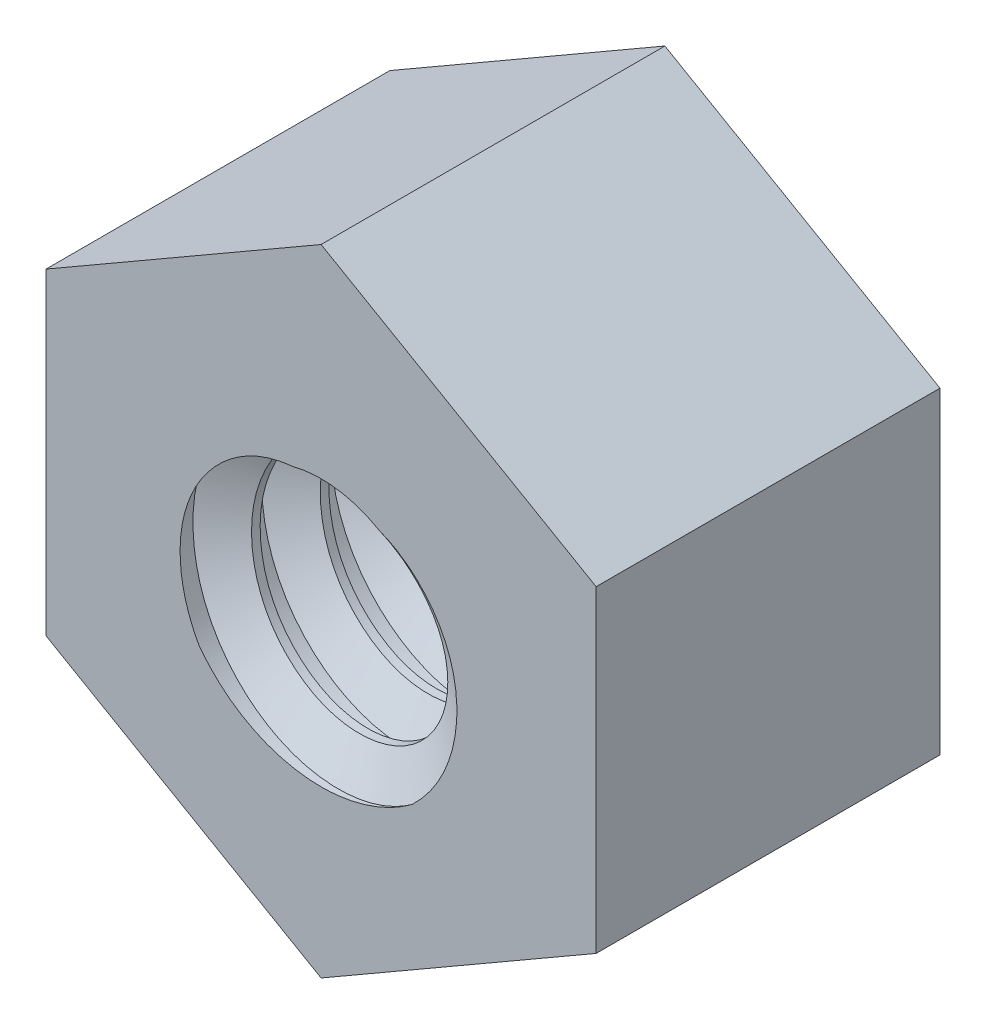
SolidWorks part; units mm, degrees
ref_plane "Front Plane" through (0, 0, 0) normal (0, 0, 1) x (1, 0, 0)
ref_plane "Top Plane" through (0, 0, 0) normal (0, 1, 0) x (1, 0, 0)
ref_plane "Right Plane" through (0, 0, 0) normal (1, 0, 0) x (0, 0, -1)
sketch "Sketch2" plane through (0, 0, 0) normal (0, 0, 1) x (1, 0, 0)
  line L1 (0, -4.6188) -> (4, -2.3094)
  line L2 (4, -2.3094) -> (4, 2.3094)
  line L3 (4, 2.3094) -> (0, 4.6188)
  line L4 (0, 4.6188) -> (-4, 2.3094)
  line L5 (-4, 2.3094) -> (-4, -2.3094)
  line L6 (-4, -2.3094) -> (0, -4.6188)
  circle A0 centre (0, 0) radius 4 construction
  circle A1 centre (0, 0) radius 1.67
  dimension "D2" = 3.34
  dimension "D1" = 8
extrude "Boss-Extrude1" add sketch "Sketch2" against normal blind 5
sketch "Sketch3" plane through (0, 0, 0) normal (0, 1, 0) x (1, 0, 0)
  line L0 (0, -2.1875) -> (0, 7.1656)
thread "Thread1" pitch 1 profile "Thread Profile2" start angle 0, offset 0, length 0, pitch 1, diameter 3.34
ref_plane "Plane2" through (1.67, 0, -7.1656) normal (0, 1, 0) x (-1, 0, 0)
sketch "Thread Profile2" plane through (1.67, 0, -7.1656) normal (0, 1, 0) x (-1, 0, 0)
  line L0 (0, 0) -> (0, 1) construction
  line L11 (0, 0) -> (0, 0.875)
  line L12 (0, 0.875) -> (-0.5413, 0.5625)
  line L13 (-0.5413, 0.5625) -> (-0.5413, 0.3125)
  line L15 (-0.5413, 0.3125) -> (0, 0)
  line L17 (-0.5413, 0.4375) -> (0, 0.4375) construction
  point P2 (0, 0)
  dimension "Pitch" = 1
  dimension "Profile_Angle" = 60
  dimension "Profile_Land" = 0.25
  dimension "Profile_Height" = 0.5413
